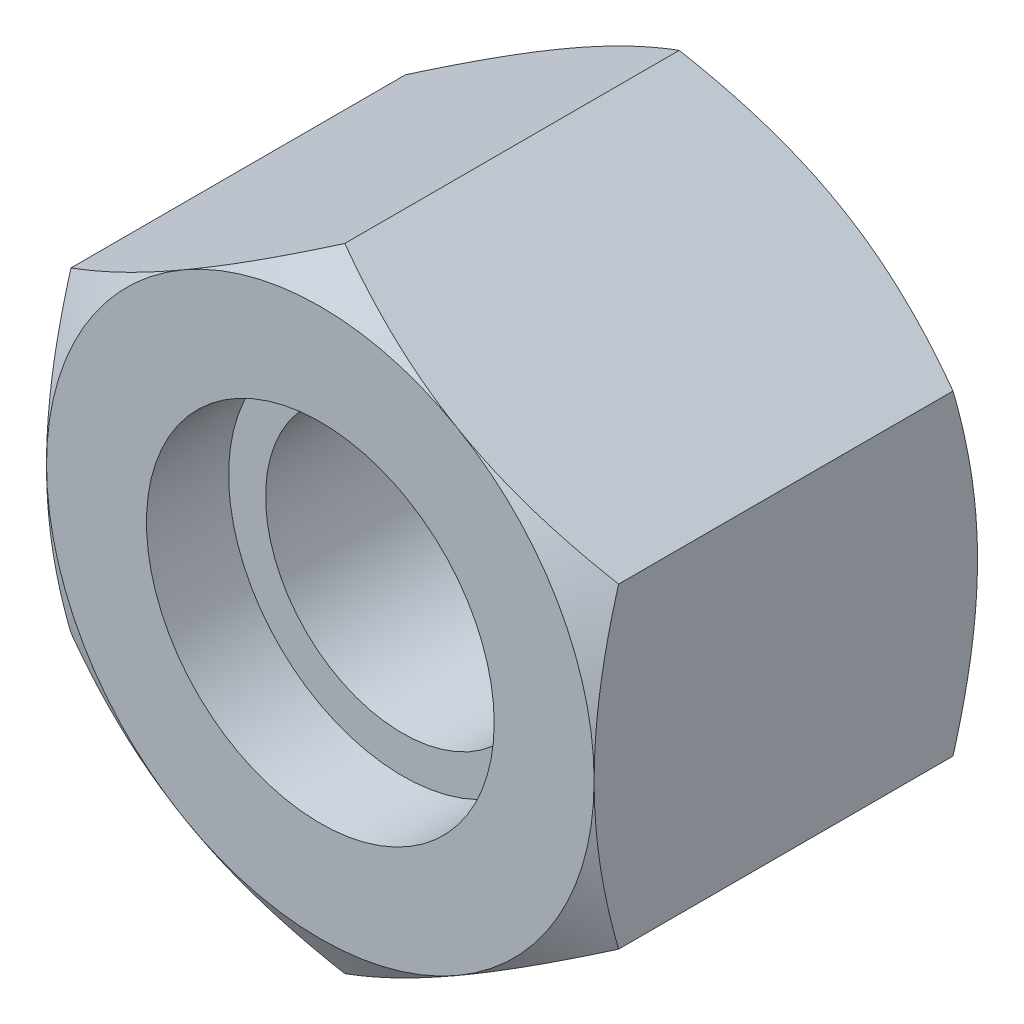
SolidWorks part; units mm, degrees
material "AISI Type 316L stainless steel"
ref_plane "Front Plane" through (0, 0, 0) normal (0, 0, 1) x (1, 0, 0)
ref_plane "Top Plane" through (0, 0, 0) normal (0, 1, 0) x (1, 0, 0)
ref_plane "Right Plane" through (0, 0, 0) normal (1, 0, 0) x (0, 0, -1)
sketch "Sketch1" plane through (0, 0, 0) normal (0, 0, 1) x (1, 0, 0)
  line L1 (0, 5.7735) -> (-5, 2.8868)
  line L2 (-5, 2.8868) -> (-5, -2.8868)
  line L3 (-5, -2.8868) -> (0, -5.7735)
  line L4 (0, -5.7735) -> (5, -2.8868)
  line L5 (5, -2.8868) -> (5, 2.8868)
  line L6 (5, 2.8868) -> (0, 5.7735)
  circle A0 centre (0, 0) radius 5 construction
  dimension "D1" = 10
extrude "Boss-Extrude1" add sketch "Sketch1" along normal blind 7
hole_wizard "M6x1.0 Tapped Hole1" positions "Sketch3" profile "Sketch2" tap size "M6x1.0" standard "Ansi Metric"
sketch "Sketch3" plane through (0, 0, 7) normal (0, 0, 1) x (1, 0, 0)
  point P0 (0, 0)
sketch "Sketch2" plane through (0, 0, 7) normal (1, 0, 0) x (0, -1, 0)
  line L0 (0, 0) -> (0, 16.5022)
  line L1 (0, 16.5022) -> (2.5, 15)
  line L2 (2.5, 15) -> (2.5, 0)
  line L5 (2.5, 0) -> (0, 0)
  line L10 (0, 16.5022) -> (-2.5, 15) construction
  line L11 (0, -6.35) -> (0, 107.95) construction
  dimension "Tap Drill Dia." = 5
  dimension "Tap Drill Depth" = 15
  dimension "Drill Angle" = 118
sketch "Sketch4" plane through (0, 0, 0) normal (1, 0, 0) x (0, 0, -1)
  line L0 (-6.5534, 5.7735) -> (-7, 5)
  line L1 (-7, 5.7735) -> (0, 5.7735) construction
  line L2 (-7, 2.8868) -> (-7, 5.7735) construction
  line L3 (-7, 5) -> (-7, 5.7735)
  line L4 (-7, 5.7735) -> (-6.5534, 5.7735)
  line L5 (0, 0) -> (-3.5, 0) construction
  line L6 (-3.5, 0) -> (-3.5, 5.7735) construction
  line L8 (0, 5.7735) -> (-0.4466, 5.7735)
  line L9 (0, 5) -> (0, 5.7735)
  line L10 (-0.4466, 5.7735) -> (0, 5)
  dimension "D1" = 30
  dimension "D2" = 10
revolve "Cut-Revolve1" cut sketch "Sketch4" angle 360 about L5
sketch "Sketch5" plane through (0, 0, 7) normal (0, 0, 1) x (1, 0, 0)
  circle A0 centre (0, 0) radius 3.175
  dimension "D1" = 6.35
extrude "Cut-Extrude1" cut sketch "Sketch5" against normal blind 1.5
